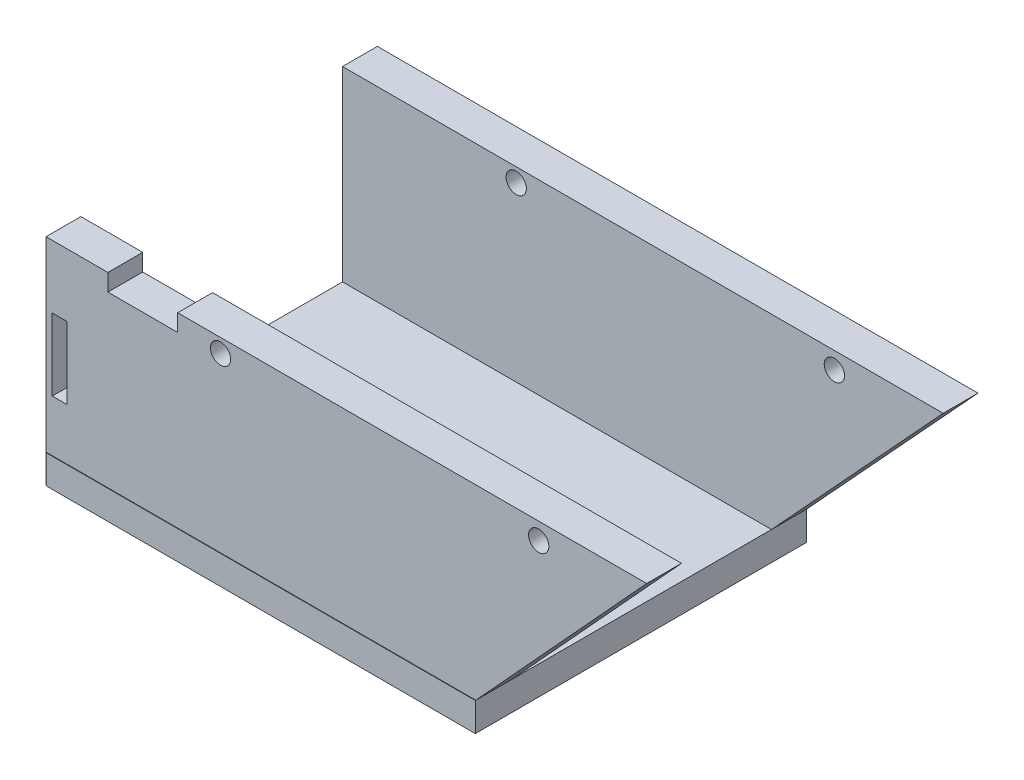
SolidWorks part; units mm, degrees
ref_plane "Front Plane" through (0, 0, 0) normal (0, 0, 1) x (1, 0, 0)
ref_plane "Top Plane" through (0, 0, 0) normal (0, 1, 0) x (1, 0, 0)
ref_plane "Right Plane" through (0, 0, 0) normal (1, 0, 0) x (0, 0, -1)
sketch "Sketch1" plane through (0, 0, 0) normal (0, 1, 0) x (1, 0, 0)
  line L1 (0, 0) -> (83.723, 0)
  line L2 (0, 0) -> (0, 46.1386)
  line L3 (0, 46.1386) -> (83.723, 46.1386)
  line L4 (83.723, 0) -> (83.723, 46.1386)
extrude "Boss-Extrude1" add sketch "Sketch1" along normal blind 4
sketch "Sketch2" plane through (0, 0, 0) normal (0, 1, 0) x (1, 0, 0)
  line L0 (83.723, 0) -> (83.723, 46.1386) construction
  line L1 (0, 46.1386) -> (83.723, 46.1386)
  line L2 (0, 46.1386) -> (0, 41.2792)
  line L3 (0, 41.2792) -> (83.723, 41.2792)
  line L4 (83.723, 46.1386) -> (83.723, 41.2792)
  line L5 (-0.1212, 4.9258) -> (83.6018, 4.9258)
  line L6 (-0.1212, 4.9258) -> (-0.1212, 0.0664)
  line L7 (-0.1212, 0.0664) -> (83.6018, 0.0664)
  line L8 (83.6018, 4.9258) -> (83.6018, 0.0664)
extrude "Boss-Extrude2" add sketch "Sketch2" along normal blind 30
sketch "Sketch3" plane through (0, 0, -0.0664) normal (0, 0, 1) x (1, 0, 0)
  line L0 (83.6018, 30) -> (83.6018, 4)
  line L1 (83.6018, 4) -> (60.8853, 4)
  line L2 (0, 4) -> (83.6018, 4) construction
  line L3 (60.8853, 4) -> (83.6018, 30)
extrude "Cut-Extrude10" cut sketch "Sketch3" against normal blind 18
sketch "Sketch6" plane through (0, 0, -41.2792) normal (0, 0, 1) x (1, 0, 0)
  line L0 (83.723, 30) -> (59.7907, 4)
  line L1 (0, 4) -> (83.723, 4) construction
  line L2 (59.7907, 4) -> (83.723, 4)
  line L3 (83.723, 4) -> (83.723, 30)
extrude "Cut-Extrude11" cut sketch "Sketch6" against normal blind 18
sketch "Sketch7" plane through (0, 0, 0) normal (0, 0, 1) x (1, 0, 0)
  line L0 (0, 4) -> (83.723, 4) construction
  line L1 (60.9771, 4) -> (83.723, 4)
  line L2 (60.9771, 4) -> (60.9771, 0)
  line L3 (60.9771, 0) -> (83.723, 0)
  line L4 (83.723, 4) -> (83.723, 0)
extrude "Cut-Extrude14" cut sketch "Sketch7" against normal blind 54
sketch "Sketch8" plane through (0, 0, 0) normal (0, -1, 0) x (1, 0, 0)
  line L1 (28.6392, -9.0958) -> (17.5877, -9.0958)
  line L2 (28.6392, -9.0958) -> (28.6392, -19.494)
  line L3 (28.6392, -19.494) -> (17.5877, -19.494)
  line L4 (17.5877, -9.0958) -> (17.5877, -19.494)
  point P4 (0, 0)
  point P5 (0, 0)
  point P6 (0, 0)
extrude "Cut-Extrude15" cut sketch "Sketch8" against normal blind 2 contours L2 L1 L4 L3
sketch "Sketch9" plane through (0, 0, -0.0664) normal (0, 0, 1) x (1, 0, 0)
  line L0 (-0.1212, 30) -> (83.6018, 30) construction
  line L1 (18.2356, 27.6229) -> (8.5041, 27.6229)
  line L2 (18.2356, 27.6229) -> (18.2356, 30)
  line L3 (18.2356, 30) -> (8.5041, 30)
  line L4 (8.5041, 27.6229) -> (8.5041, 30)
extrude "Cut-Extrude16" cut sketch "Sketch9" against normal blind 8 contours L2 L1 L4 L3
sketch "Sketch10" plane through (0, 0, -0.0664) normal (0, 0, 1) x (1, 0, 0)
  line L1 (2.8163, 11.1989) -> (0.7473, 11.1989)
  line L2 (2.8163, 11.1989) -> (2.8163, 21.2325)
  line L3 (2.8163, 21.2325) -> (0.7473, 21.2325)
  line L4 (0.7473, 11.1989) -> (0.7473, 21.2325)
extrude "Cut-Extrude17" cut sketch "Sketch10" against normal blind 8
sketch "Sketch11" plane through (0, 0, -46.1386) normal (0, 0, -1) x (-1, 0, 0)
  line L1 (-60.9771, 0) -> (-59.7907, 0)
  line L2 (-60.9771, 0) -> (-60.9771, 4)
  line L3 (-60.9771, 4) -> (-59.7907, 4)
  line L4 (-59.7907, 0) -> (-59.7907, 4)
extrude "Cut-Extrude18" cut sketch "Sketch11" against normal blind 47
sketch "Sketch12" plane through (0, 0, -4.9258) normal (0, 0, -1) x (-1, 0, 0)
  line L0 (-59.7907, 4) -> (-83.4782, 29.8585)
  line L1 (-83.6018, 30) -> (-60.8853, 4) construction
  line L2 (-83.4782, 29.8585) -> (-60.8853, 4)
  line L3 (-60.8853, 4) -> (-59.7907, 4)
extrude "Cut-Extrude19" cut sketch "Sketch12" against normal blind 47
sketch "Sketch13" plane through (0, 0, -0.0664) normal (0, 0, 1) x (1, 0, 0)
  circle A0 centre (68.5586, 27.6458) radius 1.4145
  circle A2 centre (24.2085, 28.0643) radius 1.4145
extrude "Cut-Extrude20" cut sketch "Sketch13" against normal blind 58
